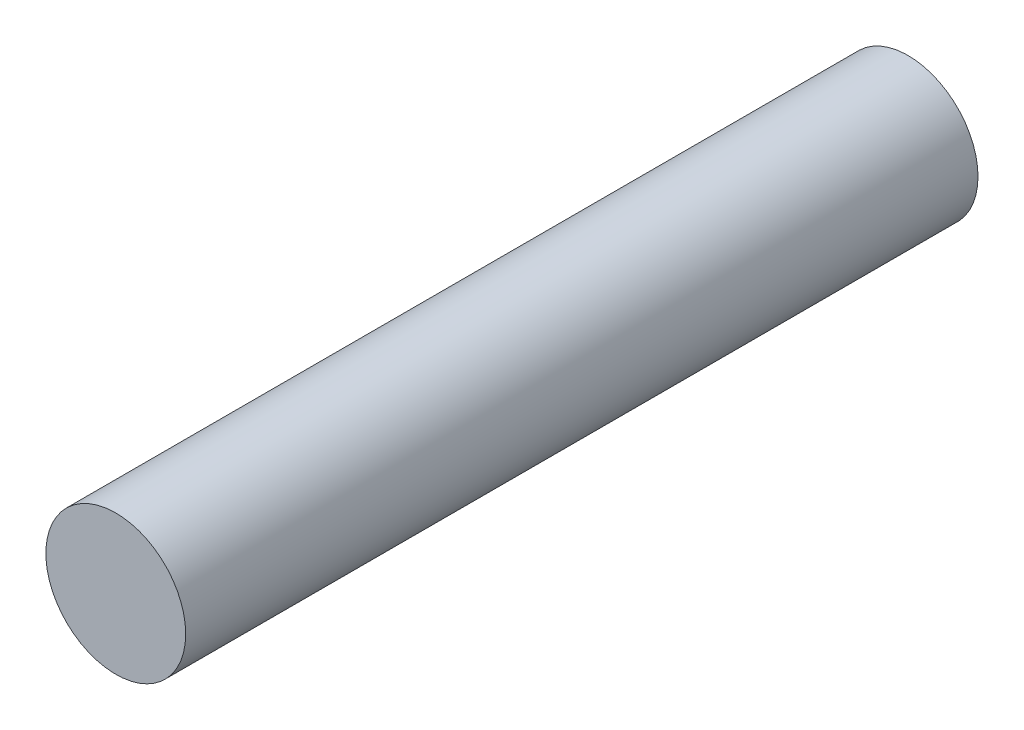
SolidWorks part; units mm, degrees
ref_plane "Plan de face" through (0, 0, 0) normal (0, 0, 1) x (1, 0, 0)
ref_plane "Plan de dessus" through (0, 0, 0) normal (0, 1, 0) x (1, 0, 0)
ref_plane "Plan de droite" through (0, 0, 0) normal (1, 0, 0) x (0, 0, -1)
sketch "Esquisse1" plane through (0, 0, 0) normal (0, 0, 1) x (1, 0, 0)
  circle A0 centre (0, 0) radius 3
  dimension "D1" = 6
extrude "Boss.-Extru.1" add sketch "Esquisse1" along normal blind 34
